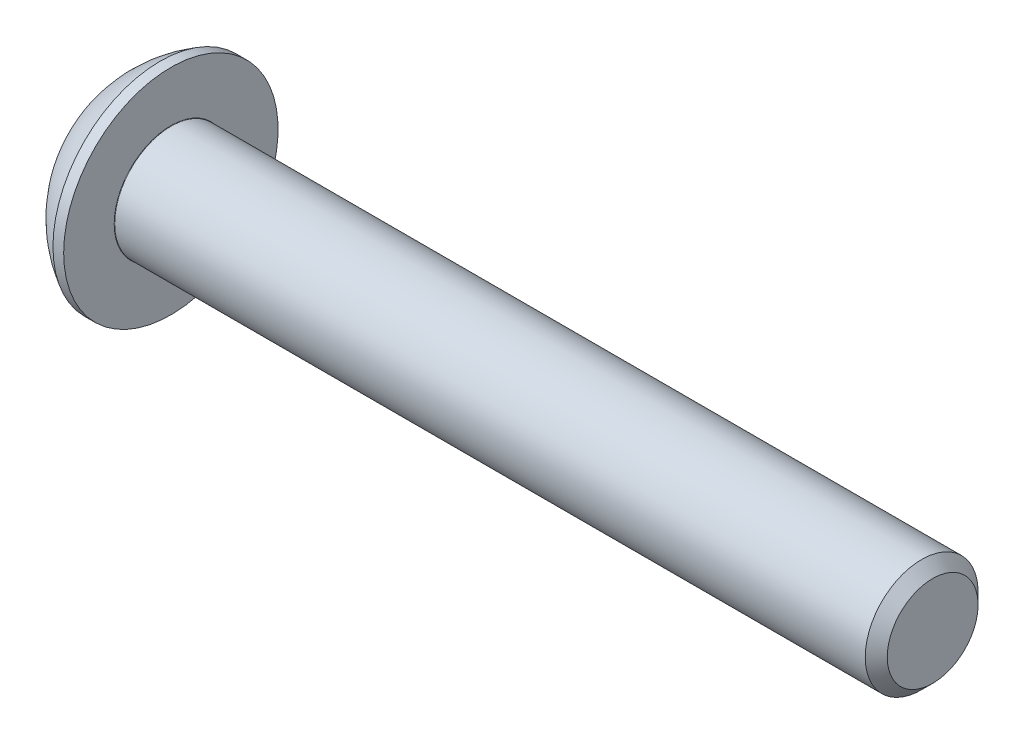
SolidWorks part; units mm, degrees
ref_plane "Plane1" through (0, 0, 0) normal (0, 0, 1) x (1, 0, 0)
ref_plane "Plane2" through (0, 0, 0) normal (0, 1, 0) x (1, 0, 0)
ref_plane "Plane3" through (0, 0, 0) normal (1, 0, 0) x (0, 0, -1)
sketch "BodySke" plane through (0, 0, 0) normal (0, 0, 1) x (1, 0, 0)
  line L0 (29.2, 0) -> (29.2, 1.61)
  line L1 (28.81, 2) -> (2.2, 2)
  line L2 (2.2, 2) -> (2.2, 3.8)
  line L3 (2.2, 3.8) -> (1.82, 3.8)
  line L4 (0, 0) -> (101.6, 0) construction
  line L5 (2.2, -3.8) -> (1.82, -3.8) construction
  line L6 (55.6768, -2) -> (2.2, -2) construction
  line L7 (29.2, 0) -> (0, 0)
  line L8 (0, 1.9) -> (0, -1.9) construction
  line L9 (0, 0) -> (0, 1.9)
  line L10 (29.2, 1.61) -> (28.81, 2)
  line L11 (29.2, -1.61) -> (28.81, -2) construction
  line L12 (2.9, 9.525) -> (2.9, -2) construction
  line L13 (9.2, 9.525) -> (9.2, -2) construction
  arc A1 (0, 1.9) -> (1.82, 3.8) centre (3.8853, 0) cw
  dimension "Diameter" = 4
  dimension "Length" = 27
  dimension "Head_dia" = 7.6
  dimension "D1" = 3.8
  dimension "Head_ht" = 2.2
  dimension "Head_side_ht" = 0.38
  dimension "Minor_dia" = 3.22
  dimension "Advance" = 0.7
  dimension "Thread_nom" = 20
  dimension "D2" = 45
revolve "BaseBody" add sketch "BodySke" angle 360 about L4
cosmetic thread "Representação de rosca1" parameters "D1"=20, "D2"=3
fillet "Fillet1" radius 0.01 1 edges at (2.2, 0, 2)
sketch "Sketch2" plane through (0, 0, 0) normal (0, 0, 1) x (1, 0, 0)
  line L0 (0, 1.25) -> (1.3, 1.25)
  line L1 (1.3, 1.25) -> (2.0217, 0)
  line L3 (2.0217, 0) -> (0, 0)
  line L4 (0, 0) -> (0, 1.25)
  line L5 (0, -1.25) -> (1.3, -1.25) construction
  line L6 (0, 0) -> (47.625, 0) construction
  dimension "D2" = 60
  dimension "PreBroach_depth" = 1.3
  dimension "PreBroach_dia" = 2.5
revolve "PreBroach" cut sketch "Sketch2" angle 360 about L6
sketch "Sketch3" plane through (0, 0, 0) normal (1, 0, 0) x (0, 0, -1)
  line L0 (-1.25, -0.7217) -> (-1.25, 0.7217)
  line L1 (-1.25, 0.7217) -> (0, 1.4434)
  line L2 (0, 1.4434) -> (1.25, 0.7217)
  line L3 (1.25, 0.7217) -> (1.25, -0.7217)
  line L4 (1.25, -0.7217) -> (0, -1.4434)
  line L5 (0, -1.4434) -> (-1.25, -0.7217)
  dimension "Hex_size" = 2.5
  dimension "D3" = 2.5
  dimension "D1" = 1.25
  dimension "D2" = 1.25
extrude "Hex" cut sketch "Sketch3" along normal blind 1.3
equation "\"D1@BodySke\" = \"Head_dia@BodySke\" * .5"
equation "\"D1@Sketch3\" = \"Hex_size@Sketch3\" / 2"
equation "\"D2@Sketch3\" = \"D1@Sketch3\""
equation "\"D3@Sketch3\" = \"Hex_size@Sketch3\""
